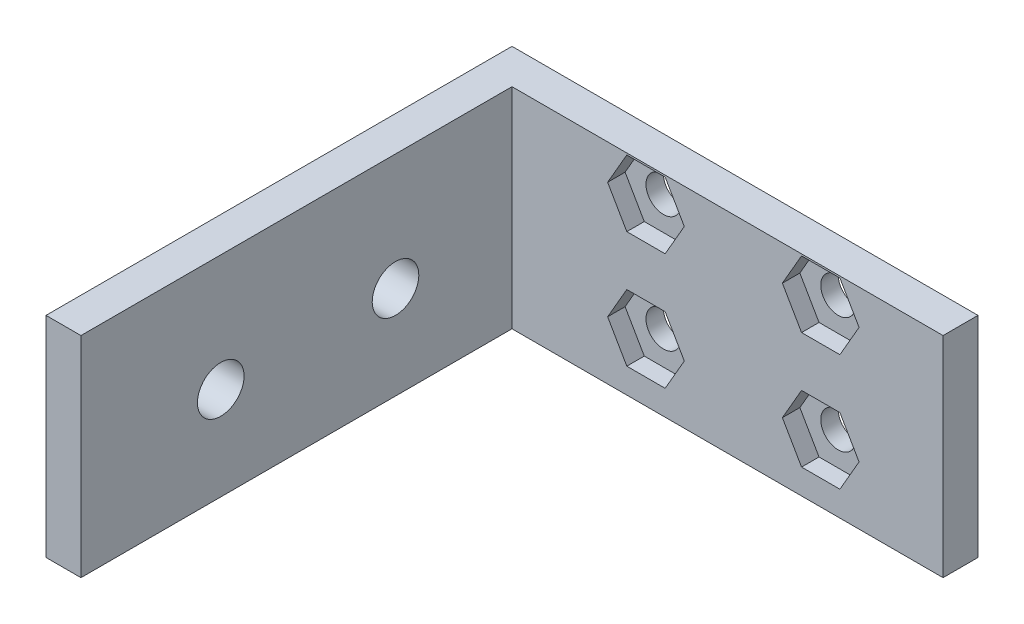
SolidWorks part; units mm, degrees
ref_plane "Plan de face" through (0, 0, 0) normal (0, 0, 1) x (1, 0, 0)
ref_plane "Plan de dessus" through (0, 0, 0) normal (0, 1, 0) x (1, 0, 0)
ref_plane "Plan de droite" through (0, 0, 0) normal (1, 0, 0) x (0, 0, -1)
sketch "Esquisse1" plane through (0, 0, 0) normal (0, 0, 1) x (1, 0, 0)
  line L1 (0, 0) -> (40, 0)
  line L2 (0, 0) -> (0, 18)
  line L3 (0, 18) -> (40, 18)
  line L4 (40, 0) -> (40, 18)
  dimension "D1" = 18
  dimension "D2" = 40
extrude "Boss.-Extru.1" add sketch "Esquisse1" along normal blind 3
sketch "Esquisse2" plane through (0, 0, 3) normal (0, 0, 1) x (1, 0, 0)
  line L0 (0, 0) -> (40, 0) construction
  line L1 (0, 18) -> (3, 18)
  line L2 (0, 18) -> (0, 0)
  line L3 (0, 0) -> (3, 0)
  line L4 (3, 18) -> (3, 0)
  dimension "D1" = 3
extrude "Boss.-Extru.2" add sketch "Esquisse2" along normal blind 37
sketch "Esquisse3" plane through (0, 0, 3) normal (0, 0, 1) x (1, 0, 0)
  line L0 (3, 0) -> (3, 18) construction
  line L4 (3, 0) -> (40, 0) construction
  circle A0 centre (14.5, 15) radius 1.5
  circle A1 centre (29.5, 15) radius 1.5
  circle A2 centre (14.5, 5) radius 1.5
  circle A3 centre (29.5, 5) radius 1.5
  dimension "D2" = 3
  dimension "D3" = 3
  dimension "D4" = 3
  dimension "D5" = 15
  dimension "D1" = 3
  dimension "D6" = 10
  dimension "D7" = 11.5
  dimension "D8" = 11.5
  dimension "D9" = 10
  dimension "D10" = 15
  dimension "D11" = 5
  dimension "D12" = 5
extrude "Enlèv. mat.-Extru.1" cut sketch "Esquisse3" against normal through all
sketch "Esquisse4" plane through (3, 0, 0) normal (1, 0, 0) x (0, 0, -1)
  line L0 (-40, 18) -> (-3, 18) construction
  line L1 (-3, 0) -> (-3, 18) construction
  circle A0 centre (-28, 8) radius 2
  circle A1 centre (-13, 8) radius 2
  dimension "D1" = 4
  dimension "D2" = 4
  dimension "D3" = 15
  dimension "D4" = 10
  dimension "D5" = 10
  dimension "D6" = 10
extrude "Enlèv. mat.-Extru.2" cut sketch "Esquisse4" against normal through all
sketch "Esquisse5" plane through (0, 0, 3) normal (0, 0, 1) x (1, 0, 0)
  line L0 (3, 0) -> (40, 0) construction
  line L1 (12.8546, 7.85) -> (11.2091, 5)
  line L2 (11.2091, 5) -> (12.8546, 2.15)
  line L3 (12.8546, 2.15) -> (16.1454, 2.15)
  line L4 (16.1454, 2.15) -> (17.7909, 5)
  line L5 (17.7909, 5) -> (16.1454, 7.85)
  line L6 (16.1454, 7.85) -> (12.8546, 7.85)
  line L7 (27.8546, 17.85) -> (26.2091, 15)
  line L8 (26.2091, 15) -> (27.8546, 12.15)
  line L9 (27.8546, 12.15) -> (31.1454, 12.15)
  line L10 (31.1454, 12.15) -> (32.7909, 15)
  line L11 (32.7909, 15) -> (31.1454, 17.85)
  line L12 (31.1454, 17.85) -> (27.8546, 17.85)
  line L13 (27.8546, 7.85) -> (26.2091, 5)
  line L14 (26.2091, 5) -> (27.8546, 2.15)
  line L15 (27.8546, 2.15) -> (31.1454, 2.15)
  line L16 (31.1454, 2.15) -> (32.7909, 5)
  line L17 (32.7909, 5) -> (31.1454, 7.85)
  line L18 (31.1454, 7.85) -> (27.8546, 7.85)
  line L19 (12.8546, 17.85) -> (11.2091, 15)
  line L20 (11.2091, 15) -> (12.8546, 12.15)
  line L21 (12.8546, 12.15) -> (16.1454, 12.15)
  line L22 (16.1454, 12.15) -> (17.7909, 15)
  line L23 (17.7909, 15) -> (16.1454, 17.85)
  line L24 (16.1454, 17.85) -> (12.8546, 17.85)
  circle A0 centre (14.5, 5) radius 2.85 construction
  circle A1 centre (29.5, 15) radius 2.85 construction
  circle A2 centre (29.5, 5) radius 2.85 construction
  circle A3 centre (14.5, 15) radius 2.85 construction
  dimension "D1" = 5.7
  dimension "D2" = 5.7
  dimension "D3" = 5.7
  dimension "D4" = 5.7
extrude "Enlèv. mat.-Extru.3" cut sketch "Esquisse5" against normal blind 1.5
